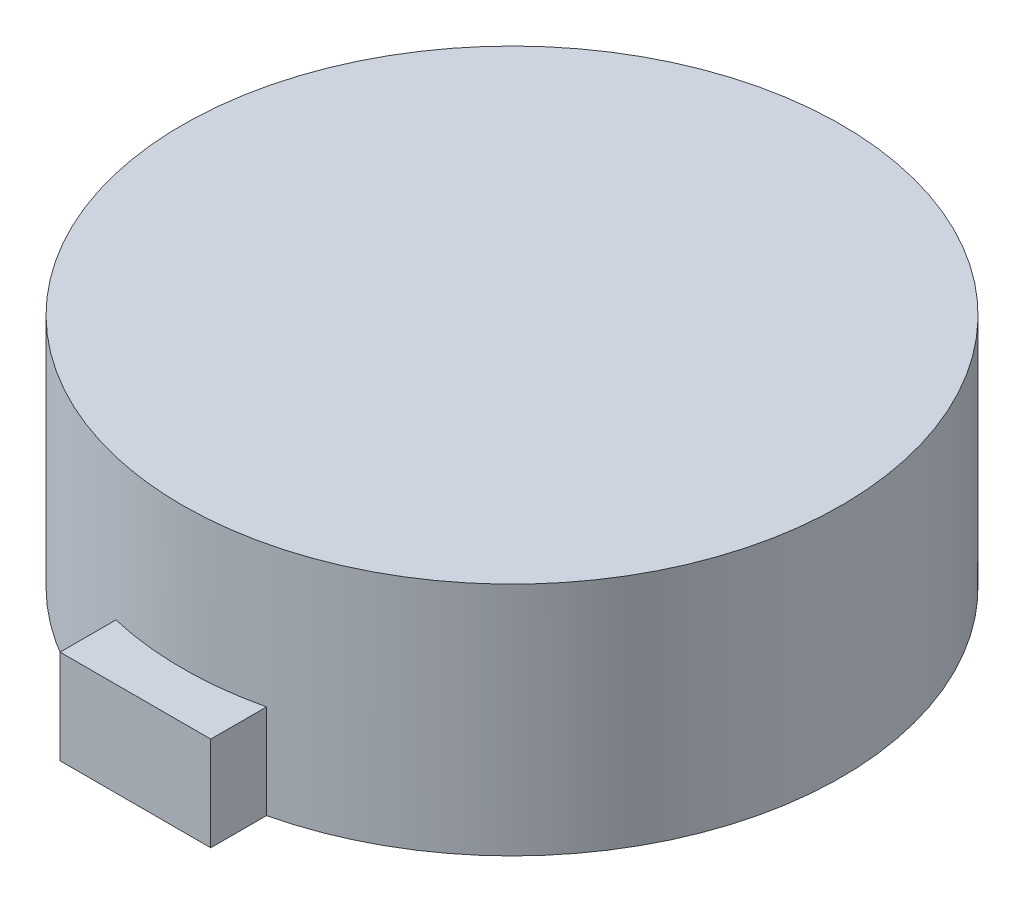
SolidWorks part; units mm, degrees
ref_plane "Front Plane" through (0, 0, 0) normal (0, 0, 1) x (1, 0, 0)
ref_plane "Top Plane" through (0, 0, 0) normal (0, 1, 0) x (1, 0, 0)
ref_plane "Right Plane" through (0, 0, 0) normal (1, 0, 0) x (0, 0, -1)
sketch "Sketch1" plane through (0, 0, 0) normal (0, 1, 0) x (1, 0, 0)
  circle A0 centre (0, 0) radius 4.445
  dimension "D1" = 8.89
extrude "Boss-Extrude1" add sketch "Sketch1" along normal blind 3.175
sketch "Sketch3" plane through (0, 0, 0) normal (0, -1, 0) x (1, 0, 0)
  line L0 (0, 0) -> (0, 5.08) construction
  line L1 (1.016, 5.08) -> (-1.016, 5.08)
  line L2 (-1.016, 5.08) -> (-1.016, 4.3273)
  line L3 (0, 5.08) -> (0, 4.445)
  line L4 (1.016, 5.08) -> (1.016, 4.3273)
  circle A0 centre (0, 0) radius 4.445 construction
  arc A1 (-1.016, 4.3273) -> (1.016, 4.3273) centre (0, 0) cw
  circle M7 centre (0, 0) radius 4.445
  dimension "D3" = 4.445
  dimension "D1" = 5.08
  dimension "D2" = 1.016
extrude "Boss-Extrude2" add sketch "Sketch3" against normal blind 1.27 contours L3 L1 L2 M7 | L4 L1 L3 M7
